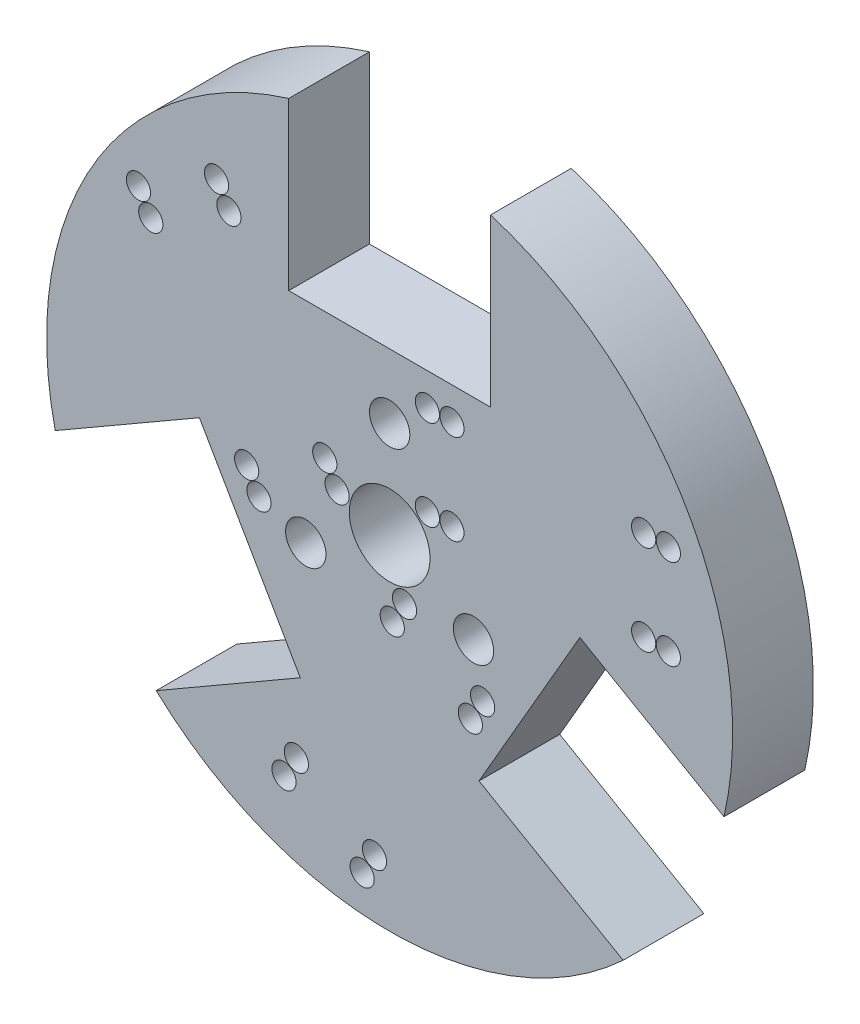
SolidWorks part; units mm, degrees
ref_plane "Front Plane" through (0, 0, 0) normal (0, 0, 1) x (1, 0, 0)
ref_plane "Top Plane" through (0, 0, 0) normal (0, 1, 0) x (1, 0, 0)
ref_plane "Right Plane" through (0, 0, 0) normal (1, 0, 0) x (0, 0, -1)
sketch "Plan" plane through (0, 0, 0) normal (0, 0, 1) x (1, 0, 0)
  line L0 (0, 0) -> (0, 60) construction
  line L1 (0, 0) -> (51.9615, -30) construction
  line L2 (0, 0) -> (-51.9615, -30) construction
  line L3 (0, 0) -> (0, 60) construction
  line L4 (0, 0) -> (51.9615, -30) construction
  line L5 (42.3527, 42.5) -> (-42.3527, 42.5) construction
  line L6 (-10, 60) -> (10, 60)
  line L7 (-10, 60) -> (-10, 25)
  line L8 (-10, 25) -> (10, 25)
  line L9 (10, 60) -> (10, 25)
  circle A0 centre (0, 0) radius 60
  circle A1 centre (0, 0) radius 55
  text T0 "Tyre"
  point P13 (0, 60)
  point P17 (-10, 42.5)
  dimension "D1" = 3
  dimension "D5" = 120
  dimension "D6" = 5
  dimension "D2" = 120
  dimension "D3" = 35
  dimension "D4" = 20
sketch "Stepper Motor" plane through (0, 0, 0) normal (0, 0, 1) x (1, 0, 0)
  line L1 (10.7429, 49.5) -> (29.7429, 49.5)
  line L2 (10.7429, 49.5) -> (10.7429, 21.5)
  line L3 (10.7429, 21.5) -> (29.7429, 21.5)
  line L4 (29.7429, 49.5) -> (29.7429, 21.5)
  line L5 (10.7429, 47) -> (0.7429, 47)
  line L6 (10.7429, 47) -> (10.7429, 38)
  line L7 (10.7429, 38) -> (0.7429, 38)
  line L8 (0.7429, 47) -> (0.7429, 38)
  line L9 (-1.5598, 42.5) -> (29.7429, 42.5) construction
  line L11 (42.3527, 42.5) -> (-42.3527, 42.5) construction
  text T0 "Stepper"
  point P11 (0.7429, 42.5)
  dimension "D1" = 28
  dimension "D2" = 19
  dimension "D3" = 9
  dimension "D4" = 10
  dimension "D5" = 2.5
sketch "DC Motor" plane through (0, 0, 0) normal (0, 0, 1) x (1, 0, 0)
  line L0 (63.4697, 76.7537) -> (25.6249, 76.7537) construction
  line L1 (38.6689, 84.3037) -> (63.6689, 84.3037)
  line L2 (38.6689, 84.3037) -> (38.6689, 69.2037)
  line L3 (38.6689, 69.2037) -> (63.6689, 69.2037)
  line L4 (63.6689, 84.3037) -> (63.6689, 69.2037)
  line L5 (28.6689, 79.8287) -> (38.6689, 79.8287)
  line L6 (28.6689, 79.8287) -> (28.6689, 73.6787)
  line L7 (28.6689, 73.6787) -> (38.6689, 73.6787)
  line L8 (38.6689, 79.8287) -> (38.6689, 73.6787)
  text T0 "DC"
  point P10 (38.6689, 76.7537)
  point P11 (38.6689, 76.7537)
  dimension "D1" = 25
  dimension "D2" = 15.1
  dimension "D3" = 10
  dimension "D4" = 6.15
sketch "Sketch4" plane through (0, 0, 0) normal (0, 0, 1) x (1, 0, 0)
  circle A0 centre (0, 0) radius 42.5
  dimension "D1" = 85
extrude "base" add sketch "Sketch4" along normal blind 10
sketch "Sketch5" plane through (0, 0, 0) normal (0, 0, 1) x (1, 0, 0)
  line L0 (0, 0) -> (0, 60) construction
  line L1 (12.5, 20) -> (-12.5, 20)
  line L2 (12.5, 20) -> (12.5, 60)
  line L3 (12.5, 60) -> (-12.5, 60)
  line L4 (-12.5, 20) -> (-12.5, 60)
  line L5 (11.0705, -20.8253) -> (23.5705, 0.8253)
  line L6 (23.5705, 0.8253) -> (58.2115, -19.1747)
  line L7 (11.0705, -20.8253) -> (45.7115, -40.8253)
  line L8 (45.7115, -40.8253) -> (58.2115, -19.1747)
  line L9 (-23.5705, 0.8253) -> (-11.0705, -20.8253)
  line L10 (-11.0705, -20.8253) -> (-45.7115, -40.8253)
  line L11 (-23.5705, 0.8253) -> (-58.2115, -19.1747)
  line L12 (-58.2115, -19.1747) -> (-45.7115, -40.8253)
  circle A0 centre (0, 0) radius 5
  point P4 (0, 20)
  point P7 (0, 60)
  point P19 (0, 0)
  dimension "D1" = 25
  dimension "D2" = 40
  dimension "D4" = 20
  dimension "D3" = 3
extrude "Tyre cut" cut sketch "Sketch5" along normal blind 10
sketch "arm" plane through (0, 0, 0) normal (0, 0, 1) x (1, 0, 0)
  line L0 (-12.5, 20) -> (12.5, 20) construction
  line L1 (12.5, 49.5) -> (29.7429, 49.5)
  line L2 (12.5, 49.5) -> (12.5, 0.8253)
  line L3 (12.5, 0.8253) -> (29.7429, 0.8253)
  line L4 (29.7429, 49.5) -> (29.7429, 0.8253)
  line L5 (4.9314, 20) -> (37.5, 20)
  line L6 (12.5, 20) -> (12.5, 40.6202) construction
  line L7 (29.7429, 49.5) -> (29.7429, 21.5) construction
  line L8 (10.7429, 49.5) -> (29.7429, 49.5) construction
  line L9 (-5.5353, -11.238) -> (-14.1567, -26.1707)
  line L10 (27.9968, -50.5081) -> (-14.1567, -26.1707)
  line L11 (36.6183, -35.5753) -> (-5.5353, -11.238)
  line L12 (36.6183, -35.5753) -> (27.9968, -50.5081)
  line L13 (-6.9647, 10.4127) -> (-15.5862, 25.3454)
  line L14 (-57.7397, 1.0081) -> (-15.5862, 25.3454)
  line L15 (-49.1183, -13.9247) -> (-6.9647, 10.4127)
  line L16 (-49.1183, -13.9247) -> (-57.7397, 1.0081)
  line L17 (4.9314, 20) -> (4.9314, 0.8253)
  line L18 (4.9314, 0.8253) -> (37.5, 0.8253)
  line L19 (37.5, 20) -> (37.5, 0.8253)
  line L20 (14.8548, -14.2707) -> (-1.751, -4.6834)
  line L21 (-1.751, -4.6834) -> (-18.0353, -32.8886)
  line L22 (14.8548, -14.2707) -> (-1.4295, -42.476)
  line L23 (-1.4295, -42.476) -> (-18.0353, -32.8886)
  line L24 (-19.7862, -5.7293) -> (-3.1805, 3.8581)
  line L25 (-3.1805, 3.8581) -> (-19.4647, 32.0633)
  line L26 (-19.7862, -5.7293) -> (-36.0705, 22.476)
  line L27 (-36.0705, 22.476) -> (-19.4647, 32.0633)
  line L29 (10.5, 20) -> (31.7429, 20)
  line L30 (10.5, 20) -> (10.5, 0.8253)
  line L31 (10.5, 0.8253) -> (31.7429, 0.8253)
  line L32 (31.7429, 20) -> (31.7429, 0.8253)
  line L33 (12.0705, -19.0933) -> (-4.5353, -9.5059)
  line L34 (1.4491, -37.4901) -> (-15.1567, -27.9028)
  line L35 (-22.5705, -0.9067) -> (-5.9647, 8.6806)
  line L36 (-33.1919, 17.4901) -> (-16.5862, 27.0775)
  circle A0 centre (0, 0) radius 5 construction
  arc A1 (41.4281, -9.4848) -> (12.5, 40.6202) centre (0, 0) ccw construction
  point P21 (0, 0)
  point P37 (0, 0)
  point P50 (0, 0)
  dimension "D5" = 2
  dimension "D6" = 2
  dimension "D1" = 3
  dimension "D4" = 3
  dimension "D7" = 3
sketch "Sketch6" plane through (0, 0, 0) normal (0, 0, 1) x (1, 0, 0)
  line L0 (0, 0) -> (0, 60) construction
  line L1 (21.1214, 16.9548) -> (21.1214, 5.6527) construction
  line L2 (4.9314, 18.6632) -> (10.5, 18.6632) construction
  line L3 (4.9314, 20) -> (4.9314, 0.8253) construction
  line L4 (10.5, 20) -> (10.5, 0.8253) construction
  line L5 (4.9314, 20) -> (37.5, 20) construction
  line L6 (4.9314, 0.8253) -> (37.5, 0.8253) construction
  line L7 (12.5, 0.8253) -> (29.7429, 0.8253) construction
  line L8 (-12.5, 20) -> (12.5, 20) construction
  circle A0 centre (7.7157, 16) radius 1.5
  circle A1 centre (7.7157, 4.8253) radius 1.5
  circle A2 centre (34.5272, 4.8253) radius 1.5
  circle A3 centre (34.5272, 16) radius 1.5
  circle A4 centre (9.9986, -14.682) radius 1.5
  circle A5 centre (0.321, -9.0947) radius 1.5
  circle A6 centre (-13.0847, -32.3141) radius 1.5
  circle A7 centre (-3.4072, -37.9014) radius 1.5
  circle A8 centre (-17.7143, -1.318) radius 1.5
  circle A9 centre (-8.0367, 4.2693) radius 1.5
  circle A10 centre (-21.4424, 27.4887) radius 1.5
  circle A11 centre (-31.12, 21.9014) radius 1.5
  circle A12 centre (0, 12) radius 2.5
  circle A13 centre (10.3923, -6) radius 2.5
  circle A14 centre (-10.3923, -6) radius 2.5
  circle A15 centre (31.4726, 16) radius 1.5
  circle A16 centre (31.4726, 4.8253) radius 1.5
  circle A17 centre (4.6726, 16) radius 1.5
  circle A18 centre (4.6726, 4.8253) radius 1.5
  circle A19 centre (11.5201, -12.0466) radius 1.5
  circle A20 centre (1.8426, -6.4592) radius 1.5
  circle A21 centre (-1.8799, -35.2561) radius 1.5
  circle A22 centre (-11.5574, -29.6687) radius 1.5
  circle A23 centre (-16.1927, -3.9534) radius 1.5
  circle A24 centre (-6.5151, 1.6339) radius 1.5
  circle A25 centre (-29.5927, 19.2561) radius 1.5
  circle A26 centre (-19.9151, 24.8434) radius 1.5
  point P11 (7.7157, 18.6632)
  point P19 (21.1214, 0.8253)
  point P43 (0, 0)
  point P44 (0, 0)
  point P54 (0, 0)
  point P80 (0, 0)
  dimension "D1" = 4
  dimension "D4" = 8
  dimension "D6" = 26.8
  dimension "D2" = 4
  dimension "D3" = 3
  dimension "D7" = 3
  dimension "D5" = 3
extrude "NUTs" cut sketch "Sketch6" along normal blind 10
